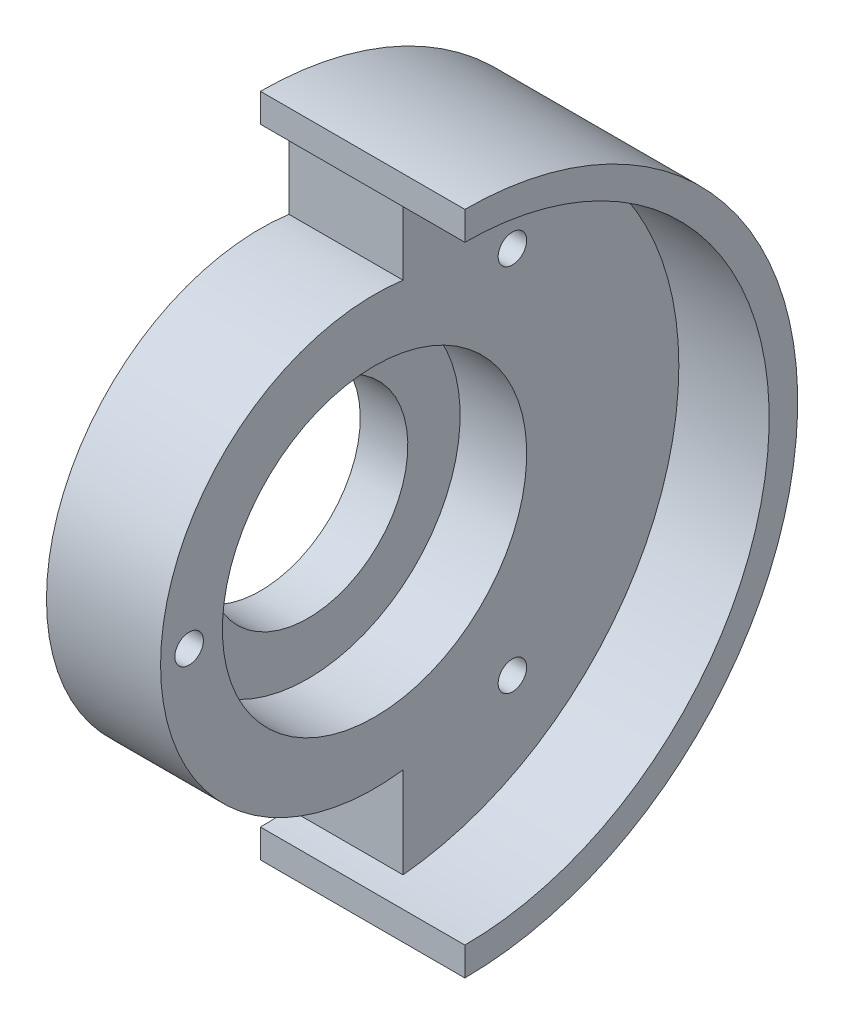
SolidWorks part; units mm, degrees
ref_plane "Front Plane" through (0, 0, 0) normal (0, 0, 1) x (1, 0, 0)
ref_plane "Top Plane" through (0, 0, 0) normal (0, 1, 0) x (1, 0, 0)
ref_plane "Right Plane" through (0, 0, 0) normal (1, 0, 0) x (0, 0, -1)
sketch "Sketch1" plane through (0, 0, 0) normal (0, 0, 1) x (1, 0, 0)
  line L0 (21.5, 35) -> (21.5, 32)
  line L1 (21.5, 32) -> (12, 32)
  line L2 (12, 32) -> (12, 16)
  line L3 (12, 16) -> (5, 16)
  line L4 (5, 16) -> (5, 10.5)
  line L5 (5, 10.5) -> (0, 10.5)
  line L6 (0, 10.5) -> (0, 35)
  line L7 (0, 35) -> (21.5, 35)
  line L8 (21.5, 0) -> (0, 0) construction
  dimension "D1" = 5
  dimension "D2" = 7
  dimension "D3" = 9.5
  dimension "D4" = 10.5
  dimension "D5" = 16
  dimension "D6" = 32
  dimension "D7" = 35
revolve "Revolve1" add sketch "Sketch1" angle 360 about L8
sketch "Sketch2" plane through (12, 0, 0) normal (1, 0, 0) x (0, 0, -1)
  line L0 (3, 22.2991) -> (3, 31.8591)
  line L1 (3, -22.2991) -> (3, -31.8591)
  line L2 (0, 35) -> (0, 32)
  line L3 (0, -32) -> (0, -35)
  arc A0 (3, 31.8591) -> (0, 32) centre (0, 0) ccw
  arc A1 (3, 22.2991) -> (3, -22.2991) centre (0, 0) ccw
  circle A2 centre (-19.5, 0) radius 1.5
  circle A3 centre (0, 0) radius 32 construction
  arc A4 (3, 22.2991) -> (3, -22.2991) centre (0, 0) ccw construction
  circle A5 centre (14.5, -19.4374) radius 1.5
  circle A6 centre (14.5, 19.4374) radius 1.5
  circle A7 centre (14.5, 19.4374) radius 1.5 construction
  circle A8 centre (-19.5, 0) radius 1.5 construction
  circle A9 centre (14.5, -19.4374) radius 1.5 construction
  arc A10 (0, 35) -> (0, -35) centre (0, 0) ccw
  circle A11 centre (0, 0) radius 35 construction
  arc A12 (0, -32) -> (3, -31.8591) centre (0, 0) ccw
extrude "Cut-Extrude1" cut sketch "Sketch2" against normal through all both and the other way through all
sketch "Sketch3" plane through (0, 0, 0) normal (-1, 0, 0) x (0, 0, 1)
  circle A0 centre (-14.5, 19.4374) radius 2.75
  circle A1 centre (19.5, 0) radius 2.75
  circle A2 centre (-14.5, -19.4374) radius 2.75
  dimension "D1" = 5.5
extrude "Cut-Extrude2" cut sketch "Sketch3" against normal blind 5
